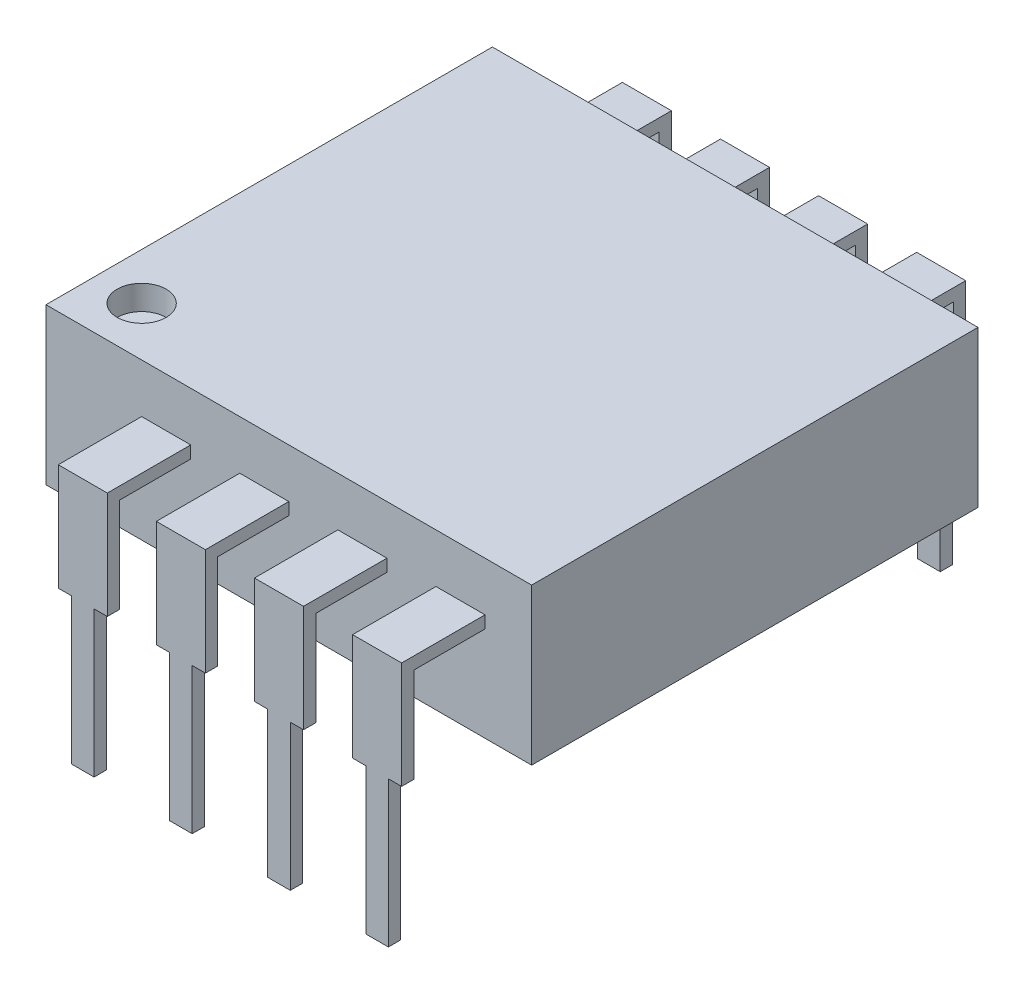
SolidWorks part; units mm, degrees
ref_plane "Front" through (0, 0, 0) normal (0, 0, 1) x (1, 0, 0)
ref_plane "Top" through (0, 0, 0) normal (0, 1, 0) x (1, 0, 0)
ref_plane "Right" through (0, 0, 0) normal (1, 0, 0) x (0, 0, -1)
sketch "Эскиз1" plane through (0, 0, 0) normal (1, 0, 0) x (0, 0, -1)
  line L0 (-4.55, 1.59) -> (4.55, 1.59)
  line L1 (4.55, 1.59) -> (4.55, -1.59)
  line L2 (4.55, -1.59) -> (-4.55, -1.59)
  line L3 (-4.55, -1.59) -> (-4.55, 1.59)
  line L4 (-4.55, 0.59) -> (-6.25, 0.59)
  line L5 (-6.25, 0.59) -> (-6.25, -4.56)
  line L6 (0, 2.9279) -> (0, -3.2868) construction
  line L7 (4.55, 0.59) -> (6.25, 0.59)
  line L8 (6.25, 0.59) -> (6.25, -4.56)
  line L9 (-4.55, 0.34) -> (-6, 0.34)
  line L10 (-6, 0.34) -> (-6, -4.56)
  line L11 (-6, -4.56) -> (-6.25, -4.56)
  line L12 (4.55, 0.34) -> (6, 0.34)
  line L13 (6, 0.34) -> (6, -4.56)
  line L14 (6, -4.56) -> (6.25, -4.56)
  point P5 (-4.55, 0)
  point P8 (0, 1.59)
  dimension "D1" = 9.1
  dimension "D2" = 3.18
  dimension "D3" = 1
  dimension "D4" = 5.15
  dimension "D5" = 12.5
  dimension "D6" = 0.25
  dimension "D7" = 0.25
extrude "Бобышка-Вытянуть1" add sketch "Эскиз1" along normal mid plane 9.9 contours L6 L0 L3 L2 | L0 L6 L2 L1 | L11 L10 L9 L3 L4 L5 | L13 L14 L8 L7 L1 L12
sketch "Эскиз2" plane through (0, 1.59, 0) normal (0, 1, 0) x (1, 0, 0)
  line L0 (4.95, -4.55) -> (-4.95, -4.55) construction
  circle A0 centre (-4, -3.55) radius 0.5
  point P2 (-3.5763, -3.6603)
  dimension "D1" = 1
  dimension "D2" = 4
  dimension "D3" = 1
extrude "Вырез-Вытянуть1" cut sketch "Эскиз2" against normal blind 0.5
sketch "Эскиз3" plane through (0, 0, 6.25) normal (0, 0, 1) x (1, 0, 0)
  line L0 (-3, 0.59) -> (-3, -1.59)
  line L1 (4.95, 0.59) -> (-4.95, 0.59) construction
  line L2 (-3, -1.59) -> (-2.73, -1.59)
  line L3 (-2.73, -1.59) -> (-2.73, -4.56)
  line L4 (4.95, -4.56) -> (-4.95, -4.56) construction
  line L5 (-2.73, -4.56) -> (-2.27, -4.56)
  line L6 (-2.27, -4.56) -> (-2.27, -1.59)
  line L7 (-2.27, -1.59) -> (-2, -1.59)
  line L8 (-2, -1.59) -> (-2, 0.59)
  line L9 (4.95, 0.59) -> (-4.95, 0.59) construction
  line L10 (-2, 0.59) -> (-3, 0.59)
  line L11 (-0.5, 2.1726) -> (-0.5, -5.2234) construction
  line L12 (-4.95, 0.59) -> (-4.95, 1.59) construction
  line L13 (4.95, -1.59) -> (-4.95, -1.59) construction
  line L14 (-1, 0.59) -> (-1, -1.59)
  line L15 (-1, -1.59) -> (-0.73, -1.59)
  line L16 (-0.73, -1.59) -> (-0.73, -4.56)
  line L17 (-0.73, -4.56) -> (-0.27, -4.56)
  line L18 (-0.27, -4.56) -> (-0.27, -1.59)
  line L19 (-0.27, -1.59) -> (0, -1.59)
  line L20 (0, -1.59) -> (0, 0.59)
  line L21 (0, 0.59) -> (-1, 0.59)
  line L22 (1, 0.59) -> (1, -1.59)
  line L23 (1, -1.59) -> (1.27, -1.59)
  line L24 (1.27, -1.59) -> (1.27, -4.56)
  line L25 (1.27, -4.56) -> (1.73, -4.56)
  line L26 (1.73, -4.56) -> (1.73, -1.59)
  line L27 (1.73, -1.59) -> (2, -1.59)
  line L28 (2, -1.59) -> (2, 0.59)
  line L29 (2, 0.59) -> (1, 0.59)
  line L30 (3, 0.59) -> (3, -1.59)
  line L31 (3, -1.59) -> (3.27, -1.59)
  line L32 (3.27, -1.59) -> (3.27, -4.56)
  line L33 (3.27, -4.56) -> (3.73, -4.56)
  line L34 (3.73, -4.56) -> (3.73, -1.59)
  line L35 (3.73, -1.59) -> (4, -1.59)
  line L36 (4, -1.59) -> (4, 0.59)
  line L37 (4, 0.59) -> (3, 0.59)
  line L38 (-4.95, 0.59) -> (-4.95, -4.56)
  line L39 (-4.95, 0.59) -> (-4.95, -4.56) construction
  line L40 (-4.95, -4.56) -> (4.95, -4.56)
  line L41 (4.95, -4.56) -> (4.95, 0.59)
  line L42 (4.95, 0.59) -> (-4.95, 0.59)
  point P11 (-2.5, -4.56)
  point P15 (-2.5, 0.59)
  line M6 (-4.95, 0.59) -> (-4.95, -4.56)
  line M7 (-4.95, -4.56) -> (4.95, -4.56)
  line M8 (4.95, -4.56) -> (4.95, 0.59)
  line M9 (4.95, 0.59) -> (-4.95, 0.59)
  dimension "D1" = 1
  dimension "D2" = 0.46
  dimension "D3" = 4.45
  dimension "D4" = 2
  dimension "D5" = 4
extrude "Вырез-Вытянуть2" cut sketch "Эскиз3" against normal up to surface (1.7 mm away) contours L3 L2 L0 M9 M6 M7 | L16 L15 L14 L8 L7 L6 M9 M7 | L24 L23 L22 L20 L19 L18 M9 M7 | L32 L31 L30 L28 L27 L26 M9 M7 | L36 L35 L34 M7 M8 M9 up to face at (0, -0.625, 4.55)
sketch "Эскиз4" plane through (0, 0, -6.25) normal (0, 0, -1) x (-1, 0, 0)
  line L0 (-3, 0.59) -> (-3, -1.59)
  line L1 (-4.95, 0.59) -> (4.95, 0.59) construction
  line L2 (-3, -1.59) -> (-2.73, -1.59)
  line L3 (-2.73, -1.59) -> (-2.73, -4.56)
  line L4 (-4.95, -4.56) -> (4.95, -4.56) construction
  line L5 (-2.73, -4.56) -> (-2.27, -4.56)
  line L6 (-2.27, -4.56) -> (-2.27, -1.59)
  line L7 (-2.27, -1.59) -> (-2, -1.59)
  line L8 (-2, -1.59) -> (-2, 0.59)
  line L9 (-2, 0.59) -> (-3, 0.59)
  line L10 (-4.95, -1.59) -> (4.95, -1.59) construction
  line L11 (-3.73, -4.56) -> (-3.27, -4.56) construction
  line L12 (-1, 0.59) -> (-1, -1.59)
  line L13 (-1, -1.59) -> (-0.73, -1.59)
  line L14 (-0.73, -1.59) -> (-0.73, -4.56)
  line L15 (-0.73, -4.56) -> (-0.27, -4.56)
  line L16 (-0.27, -4.56) -> (-0.27, -1.59)
  line L17 (-0.27, -1.59) -> (0, -1.59)
  line L18 (0, -1.59) -> (0, 0.59)
  line L19 (0, 0.59) -> (-1, 0.59)
  line L20 (1, 0.59) -> (1, -1.59)
  line L21 (1, -1.59) -> (1.27, -1.59)
  line L22 (1.27, -1.59) -> (1.27, -4.56)
  line L23 (1.27, -4.56) -> (1.73, -4.56)
  line L24 (1.73, -4.56) -> (1.73, -1.59)
  line L25 (1.73, -1.59) -> (2, -1.59)
  line L26 (2, -1.59) -> (2, 0.59)
  line L27 (2, 0.59) -> (1, 0.59)
  line L28 (3, 0.59) -> (3, -1.59)
  line L29 (3, -1.59) -> (3.27, -1.59)
  line L30 (3.27, -1.59) -> (3.27, -4.56)
  line L31 (3.27, -4.56) -> (3.73, -4.56)
  line L32 (3.73, -4.56) -> (3.73, -1.59)
  line L33 (3.73, -1.59) -> (4, -1.59)
  line L34 (4, -1.59) -> (4, 0.59)
  line L35 (4, 0.59) -> (3, 0.59)
  line L36 (-4.95, 0.59) -> (4.95, 0.59)
  line L37 (4.95, 0.59) -> (4.95, -4.56)
  line L38 (4.95, -4.56) -> (-4.95, -4.56)
  line L39 (-4.95, -4.56) -> (-4.95, 0.59)
  point P12 (-2.5, -4.56)
  point P13 (-2.5, 0.59)
  point P18 (-3.5, -4.56)
  line M5 (4.95, -4.56) -> (4.95, 0.59)
  line M6 (4.95, 0.59) -> (-4.95, 0.59)
  line M7 (-4.95, 0.59) -> (-4.95, -4.56)
  line M8 (-4.95, -4.56) -> (4.95, -4.56)
  dimension "D1" = 1
  dimension "D2" = 0.46
  dimension "D3" = 1
  dimension "D4" = 4
extrude "Вырез-Вытянуть3" cut sketch "Эскиз4" against normal up to surface (1.7 mm away) contours L3 L2 L0 M6 M7 M8 | L14 L13 L12 L8 L7 L6 M6 M8 | L22 L21 L20 L18 L17 L16 M6 M8 | L30 L29 L28 L26 L25 L24 M6 M8 | L34 L33 L32 M8 M5 M6 up to face at (0, -0.625, -4.55)
sketch "Эскиз5" plane through (0, -1.59, 0) normal (0, -1, 0) x (1, 0, 0)
  line L0 (-0.5, 6.3605) -> (-0.5, -7.1406) construction
  line L1 (-4.95, 4.55) -> (-4.95, -4.55) construction
  line L2 (6.8246, 0) -> (-7.8246, 0) construction
  line L3 (4.95, 4.55) -> (-4.95, 4.55) construction
  circle A0 centre (-0.5, 0) radius 2.8
  circle A1 centre (-0.5, 0) radius 0.4
  point P10 (-0.5, 0)
  dimension "D3" = 5.6
  dimension "D4" = 0.8
  dimension "D1" = 4.45
  dimension "D2" = 4.55
extrude "Бобышка-Вытянуть2" add sketch "Эскиз5" along normal blind 1.42
chamfer "Фаска1" distance 0.5 angle 43 1 edges at (-0.5, -3.01, -2.8)
